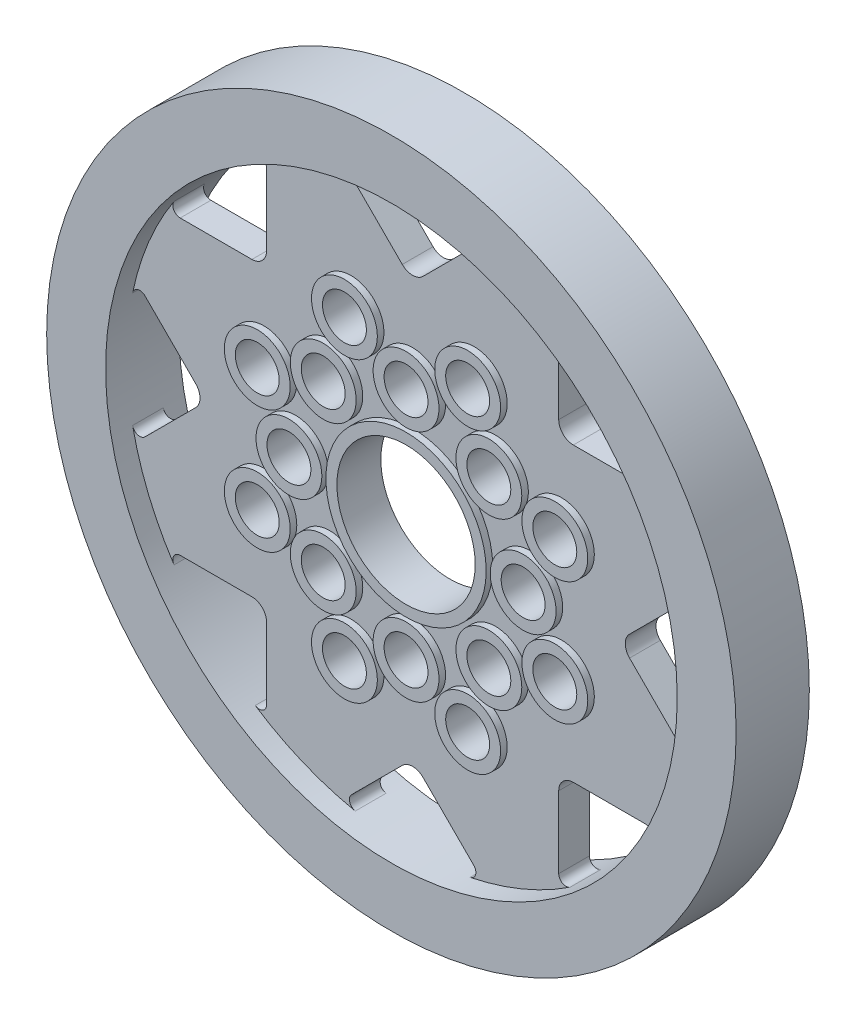
SolidWorks part; units mm, degrees
ref_plane "Piano frontale" through (0, 0, 0) normal (0, 0, 1) x (1, 0, 0)
ref_plane "Piano superiore" through (0, 0, 0) normal (0, 1, 0) x (1, 0, 0)
ref_plane "Piano destro" through (0, 0, 0) normal (1, 0, 0) x (0, 0, -1)
sketch "Schizzo1" plane through (0, 0, 0) normal (0, 0, 1) x (1, 0, 0)
  circle A0 centre (0, 0) radius 23.5494
  circle A1 centre (0, 0) radius 19.525
  dimension "D1" = 39.05
  dimension "D2" = 47.0988
extrude "Estrusione-Estrusione1" add sketch "Schizzo1" along normal mid plane 5
sketch "Schizzo2" plane through (0, 0, 0) normal (0, 0, 1) x (1, 0, 0)
  line L0 (-0.7071, 14.8179) -> (-4.1733, 18.2841)
  line L1 (0.7071, 14.8179) -> (4.1733, 18.2841)
  line L2 (0, 14.1108) -> (0, 19.525) construction
  line L3 (0, 0) -> (4.2095, 10.1627) construction
  line L4 (10.9778, 9.9778) -> (15.8797, 9.9778)
  line L5 (9.9778, 10.9778) -> (9.9778, 15.8797)
  line L6 (14.8179, -0.7071) -> (18.2841, -4.1733)
  line L7 (14.8179, 0.7071) -> (18.2841, 4.1733)
  line L8 (9.9778, -10.9778) -> (9.9778, -15.8797)
  line L9 (10.9778, -9.9778) -> (15.8797, -9.9778)
  line L10 (-0.7071, -14.8179) -> (-4.1733, -18.2841)
  line L11 (0.7071, -14.8179) -> (4.1733, -18.2841)
  line L12 (-10.9778, -9.9778) -> (-15.8797, -9.9778)
  line L13 (-9.9778, -10.9778) -> (-9.9778, -15.8797)
  line L14 (-14.8179, 0.7071) -> (-18.2841, 4.1733)
  line L15 (-14.8179, -0.7071) -> (-18.2841, -4.1733)
  line L16 (-9.9778, 10.9778) -> (-9.9778, 15.8797)
  line L17 (-10.9778, 9.9778) -> (-15.8797, 9.9778)
  circle A0 centre (0, 0) radius 4.725
  circle A1 centre (0, 0) radius 14.525 construction
  circle A2 centre (0, 0) radius 19.525 construction
  circle A3 centre (0, 8) radius 1.5
  arc A4 (-3.9201, 19.1274) -> (3.9201, 19.1274) centre (0, 0) cw
  arc A5 (-0.7071, 14.8179) -> (0.7071, 14.8179) centre (0, 15.525) ccw
  arc A6 (3.9201, 19.1274) -> (4.1733, 18.2841) centre (3.8197, 18.6376) cw
  arc A7 (-4.1733, 18.2841) -> (-3.9201, 19.1274) centre (-3.8197, 18.6376) cw
  circle A8 centre (4.2095, 10.1627) radius 1.5
  circle A9 centre (0, 0) radius 8 construction
  circle A10 centre (0, 0) radius 11 construction
  arc A11 (9.9778, 10.9778) -> (10.9778, 9.9778) centre (10.9778, 10.9778) ccw
  arc A12 (9.9778, 15.8797) -> (10.7532, 16.2971) centre (10.4778, 15.8797) cw
  arc A13 (10.7532, 16.2971) -> (16.2971, 10.7532) centre (0, 0) cw
  arc A14 (16.2971, 10.7532) -> (15.8797, 9.9778) centre (15.8797, 10.4778) cw
  circle A15 centre (10.1627, 4.2095) radius 1.5
  circle A16 centre (5.6569, 5.6569) radius 1.5
  arc A17 (14.8179, 0.7071) -> (14.8179, -0.7071) centre (15.525, 0) ccw
  arc A18 (18.2841, 4.1733) -> (19.1274, 3.9201) centre (18.6376, 3.8197) cw
  arc A19 (19.1274, 3.9201) -> (19.1274, -3.9201) centre (0, 0) cw
  arc A20 (19.1274, -3.9201) -> (18.2841, -4.1733) centre (18.6376, -3.8197) cw
  circle A21 centre (10.1627, -4.2095) radius 1.5
  circle A22 centre (8, 0) radius 1.5
  arc A23 (10.9778, -9.9778) -> (9.9778, -10.9778) centre (10.9778, -10.9778) ccw
  arc A24 (15.8797, -9.9778) -> (16.2971, -10.7532) centre (15.8797, -10.4778) cw
  arc A25 (16.2971, -10.7532) -> (10.7532, -16.2971) centre (0, 0) cw
  arc A26 (10.7532, -16.2971) -> (9.9778, -15.8797) centre (10.4778, -15.8797) cw
  circle A27 centre (4.2095, -10.1627) radius 1.5
  circle A28 centre (5.6569, -5.6569) radius 1.5
  arc A29 (0.7071, -14.8179) -> (-0.7071, -14.8179) centre (0, -15.525) ccw
  arc A30 (4.1733, -18.2841) -> (3.9201, -19.1274) centre (3.8197, -18.6376) cw
  arc A31 (3.9201, -19.1274) -> (-3.9201, -19.1274) centre (0, 0) cw
  arc A32 (-3.9201, -19.1274) -> (-4.1733, -18.2841) centre (-3.8197, -18.6376) cw
  circle A33 centre (-4.2095, -10.1627) radius 1.5
  circle A34 centre (0, -8) radius 1.5
  arc A35 (-9.9778, -10.9778) -> (-10.9778, -9.9778) centre (-10.9778, -10.9778) ccw
  arc A36 (-9.9778, -15.8797) -> (-10.7532, -16.2971) centre (-10.4778, -15.8797) cw
  arc A37 (-10.7532, -16.2971) -> (-16.2971, -10.7532) centre (0, 0) cw
  arc A38 (-16.2971, -10.7532) -> (-15.8797, -9.9778) centre (-15.8797, -10.4778) cw
  circle A39 centre (-10.1627, -4.2095) radius 1.5
  circle A40 centre (-5.6569, -5.6569) radius 1.5
  arc A41 (-14.8179, -0.7071) -> (-14.8179, 0.7071) centre (-15.525, 0) ccw
  arc A42 (-18.2841, -4.1733) -> (-19.1274, -3.9201) centre (-18.6376, -3.8197) cw
  arc A43 (-19.1274, -3.9201) -> (-19.1274, 3.9201) centre (0, 0) cw
  arc A44 (-19.1274, 3.9201) -> (-18.2841, 4.1733) centre (-18.6376, 3.8197) cw
  circle A45 centre (-10.1627, 4.2095) radius 1.5
  circle A46 centre (-8, 0) radius 1.5
  arc A47 (-10.9778, 9.9778) -> (-9.9778, 10.9778) centre (-10.9778, 10.9778) ccw
  arc A48 (-15.8797, 9.9778) -> (-16.2971, 10.7532) centre (-15.8797, 10.4778) cw
  arc A49 (-16.2971, 10.7532) -> (-10.7532, 16.2971) centre (0, 0) cw
  arc A50 (-10.7532, 16.2971) -> (-9.9778, 15.8797) centre (-10.4778, 15.8797) cw
  circle A51 centre (-4.2095, 10.1627) radius 1.5
  circle A52 centre (-5.6569, 5.6569) radius 1.5
  circle A53 centre (0, 0) radius 19.525
  point P2 (0, 14.525)
  point P18 (-4.812, 18.9228)
  point P119 (0, 0)
  dimension "D1" = 9.45
  dimension "D2" = 29.05
  dimension "D4" = 1
  dimension "D5" = 0.5
  dimension "D6" = 3
  dimension "D7" = 16
  dimension "D8" = 22
  dimension "D3" = 90
  dimension "D9" = 22.5
  dimension "D10" = 8
extrude "Estrusione-Estrusione2" add sketch "Schizzo2" along normal mid plane 2.1 contours A18 A53 A14 L4 A11 L5 A12 A6 L1 A5 L0 A7 A50 L16 A47 L17 A48 A44 L14 A41 L15 A42 A38 L12 A35 L13 A36 A32 L10 A29 L11 A30 A26 L8 A23 L9 A24 A20 L6 A17 L7 A46
sketch "Schizzo3" plane through (0, 0, 0) normal (0, 0, 1) x (1, 0, 0)
  circle A0 centre (-10.1627, 4.2095) radius 1.5 construction
  circle A1 centre (-5.6569, 5.6569) radius 1.5 construction
  circle A2 centre (-4.2095, 10.1627) radius 1.5 construction
  circle A3 centre (0, 8) radius 1.5 construction
  circle A4 centre (4.2095, 10.1627) radius 1.5 construction
  circle A5 centre (5.6569, 5.6569) radius 1.5 construction
  circle A6 centre (10.1627, 4.2095) radius 1.5 construction
  circle A7 centre (8, 0) radius 1.5 construction
  circle A8 centre (10.1627, -4.2095) radius 1.5 construction
  circle A9 centre (5.6569, -5.6569) radius 1.5 construction
  circle A10 centre (4.2095, -10.1627) radius 1.5 construction
  circle A11 centre (0, -8) radius 1.5 construction
  circle A12 centre (-4.2095, -10.1627) radius 1.5 construction
  circle A13 centre (-5.6569, -5.6569) radius 1.5 construction
  circle A14 centre (-10.1627, -4.2095) radius 1.5 construction
  circle A15 centre (-8, 0) radius 1.5 construction
  circle A16 centre (-10.1627, 4.2095) radius 1.5
  circle A17 centre (-5.6569, 5.6569) radius 1.5
  circle A18 centre (-4.2095, 10.1627) radius 1.5
  circle A19 centre (0, 8) radius 1.5
  circle A20 centre (4.2095, 10.1627) radius 1.5
  circle A21 centre (5.6569, 5.6569) radius 1.5
  circle A22 centre (10.1627, 4.2095) radius 1.5
  circle A23 centre (8, 0) radius 1.5
  circle A24 centre (10.1627, -4.2095) radius 1.5
  circle A25 centre (5.6569, -5.6569) radius 1.5
  circle A26 centre (4.2095, -10.1627) radius 1.5
  circle A27 centre (0, -8) radius 1.5
  circle A28 centre (-4.2095, -10.1627) radius 1.5
  circle A29 centre (-5.6569, -5.6569) radius 1.5
  circle A30 centre (-10.1627, -4.2095) radius 1.5
  circle A31 centre (-8, 0) radius 1.5
  circle A32 centre (0, 0) radius 4.725 construction
  circle A33 centre (0, 0) radius 4.725
  circle A34 centre (-10.1627, 4.2095) radius 2.25
  circle A35 centre (-5.6569, 5.6569) radius 2.25
  circle A36 centre (-4.2095, 10.1627) radius 2.25
  circle A37 centre (0, 8) radius 2.25
  circle A38 centre (4.2095, 10.1627) radius 2.25
  circle A39 centre (5.6569, 5.6569) radius 2.25
  circle A40 centre (10.1627, 4.2095) radius 2.25
  circle A41 centre (8, 0) radius 2.25
  circle A42 centre (0, 0) radius 5.475
  circle A43 centre (5.6569, -5.6569) radius 2.25
  circle A44 centre (10.1627, -4.2095) radius 2.25
  circle A45 centre (0, -8) radius 2.25
  circle A46 centre (-5.6569, -5.6569) radius 2.25
  circle A47 centre (-8, 0) radius 2.25
  circle A48 centre (-10.1627, -4.2095) radius 2.25
  circle A49 centre (-4.2095, -10.1627) radius 2.25
  circle A50 centre (4.2095, -10.1627) radius 2.25
  dimension "D1" = 0.75
  dimension "D2" = 0.75
extrude "Estrusione-Estrusione3" add sketch "Schizzo3" along normal mid plane 3
